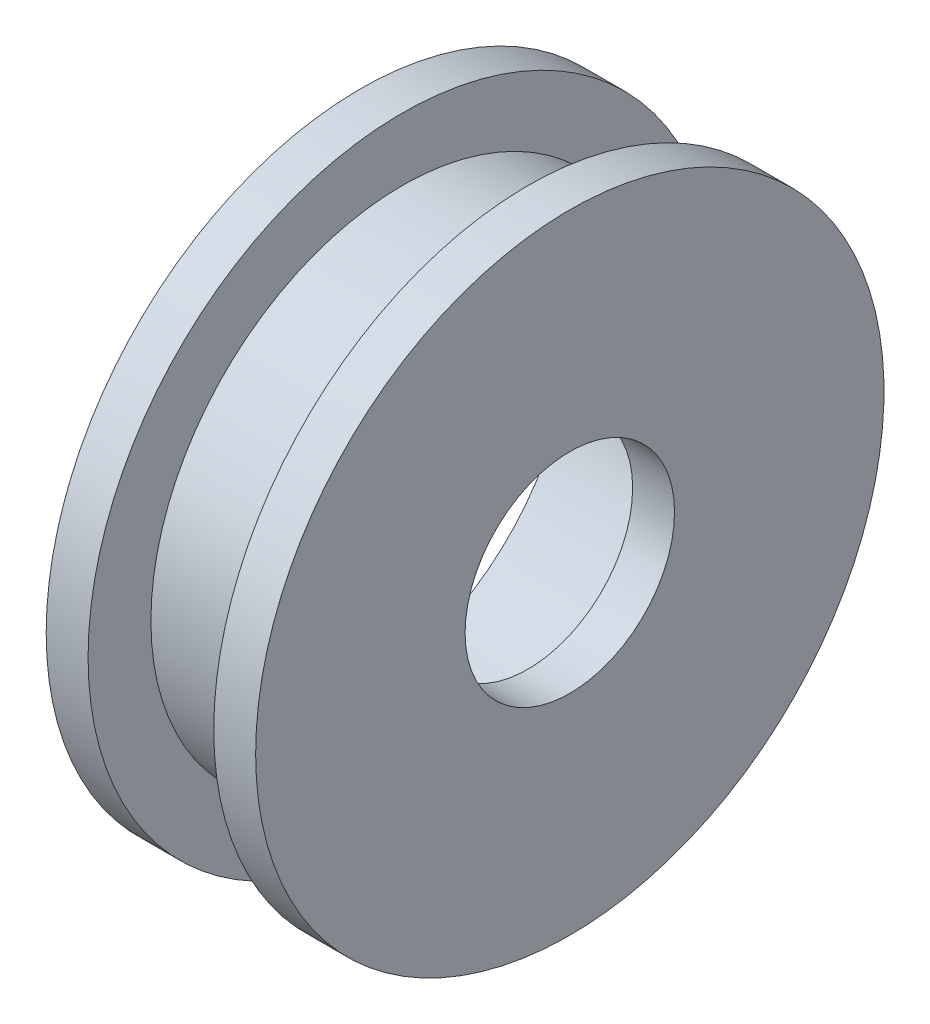
SolidWorks part; units mm, degrees
ref_plane "Plan de face" through (0, 0, 0) normal (0, 0, 1) x (1, 0, 0)
ref_plane "Plan de dessus" through (0, 0, 0) normal (0, 1, 0) x (1, 0, 0)
ref_plane "Plan de droite" through (0, 0, 0) normal (1, 0, 0) x (0, 0, -1)
sketch "Esquisse1" plane through (0, 0, 0) normal (0, 0, 1) x (1, 0, 0)
  line L0 (0, 0) -> (19.9138, 0) construction
  line L1 (-4, -7.5) -> (-4, -6)
  line L2 (-4, -6) -> (-1, -6)
  line L3 (-1, -6) -> (-1, -7.5)
  line L4 (-1, -7.5) -> (0, -7.5)
  line L5 (0, -7.5) -> (0, -2.5)
  line L6 (0, -2.5) -> (-1, -2.5)
  line L7 (-1, -2.5) -> (-1, -5)
  line L8 (-1, -5) -> (-5, -5)
  line L9 (-5, -5) -> (-5, -7.5)
  line L10 (-5, -7.5) -> (-4, -7.5)
  dimension "D1" = 12
  dimension "D2" = 3
  dimension "D3" = 1
  dimension "D4" = 1
  dimension "D5" = 5
  dimension "D6" = 1
  dimension "D7" = 10
  dimension "D8" = 15
revolve "Révolution1" add sketch "Esquisse1" angle 360 about L0
